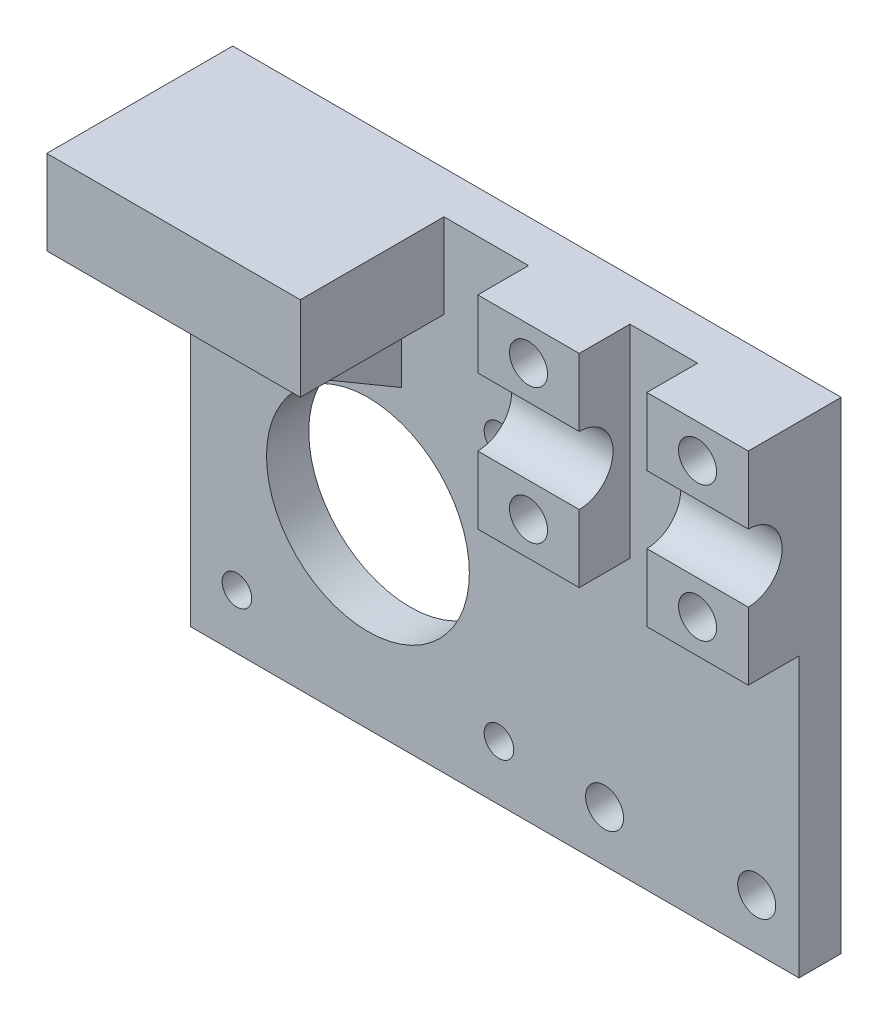
SolidWorks part; units mm, degrees
material "Printed PLA"
ref_plane "Front Plane" through (0, 0, 0) normal (0, 0, 1) x (1, 0, 0)
ref_plane "Top Plane" through (0, 0, 0) normal (0, 1, 0) x (1, 0, 0)
ref_plane "Right Plane" through (0, 0, 0) normal (1, 0, 0) x (0, 0, -1)
sketch "Sketch1" plane through (0, 0, 0) normal (0, 0, 1) x (1, 0, 0)
  line L0 (-56, 28.5) -> (16, -28.5) construction
  line L1 (-56, 28.5) -> (16, 28.5)
  line L2 (-56, 28.5) -> (-56, -28.5)
  line L3 (-56, -28.5) -> (16, -28.5)
  line L4 (16, 28.5) -> (16, -28.5)
  line L5 (-20, 0) -> (0, 0) construction
  dimension "D1" = 72
  dimension "D2" = 57
  dimension "D3" = 20
extrude "Boss-Extrude1" add sketch "Sketch1" along normal blind 5
sketch "Sketch3" plane through (16, 0, 0) normal (1, 0, 0) x (0, 0, -1)
  line L0 (-5, 28.5) -> (-11, 28.5)
  line L1 (-11, 28.5) -> (-11, 20.5)
  line L2 (-11, 12.5) -> (-11, 4.5)
  line L3 (-11, 4.5) -> (-5, 4.5)
  line L4 (-5, -28.5) -> (-5, 28.5) construction
  line L5 (-5, 4.5) -> (-5, 28.5)
  arc A0 (-11, 20.5) -> (-11, 12.5) centre (-11, 16.5) cw
  dimension "D1" = 4
  dimension "D2" = 8
  dimension "D3" = 6
extrude "Boss-Extrude2" add sketch "Sketch3" against normal blind 12
sketch "Sketch5" plane through (0, 0, 11) normal (0, 0, 1) x (1, 0, 0)
  line L0 (10, 8.5) -> (10, 24.5) construction
  line L1 (10, 16.5) -> (16, 16.5) construction
  line L2 (16, 12.5) -> (16, 20.5) construction
  line L3 (10, 24.5) -> (10, 28.5) construction
  line L4 (4, 28.5) -> (16, 28.5) construction
  circle A0 centre (10, 24.5) radius 2.25
  circle A1 centre (10, 8.5) radius 2.25
  dimension "D1" = 4.5
  dimension "D2" = 16
extrude "Cut-Extrude2" cut sketch "Sketch5" against normal through all
mirror "Mirror1" about plane through (0, 0, 0) normal (1, 0, 0) of "Cut-Extrude2", "Boss-Extrude2"
sketch "Sketch4" plane through (0, 0, 5) normal (0, 0, 1) x (1, 0, 0)
  line L0 (-56, -28.5) -> (16, -28.5) construction
  line L1 (-35, -6.5) -> (-35, -28.5) construction
  line L2 (-50.5, -22) -> (-50.5, 9) construction
  line L3 (-50.5, 9) -> (-19.5, 9) construction
  line L4 (-19.5, 9) -> (-19.5, -22) construction
  line L5 (-19.5, -22) -> (-50.5, -22) construction
  line L6 (-50.5, -22) -> (-19.5, 9) construction
  line L7 (-56, 28.5) -> (-56, -28.5) construction
  circle A0 centre (-35, -6.5) radius 12
  circle A1 centre (-50.5, 9) radius 1.75
  circle A2 centre (-19.5, 9) radius 1.75
  circle A3 centre (-19.5, -22) radius 1.75
  circle A4 centre (-50.5, -22) radius 1.75
  dimension "D2" = 24
  dimension "D4" = 3.5
  dimension "D1" = 22
  dimension "D3" = 31
  dimension "D5" = 21
extrude "Cut-Extrude1" cut sketch "Sketch4" against normal through all
sketch "Sketch6" plane through (0, 0, 5) normal (0, 0, 1) x (1, 0, 0)
  line L0 (11, -22.5) -> (-7, -22.5) construction
  line L1 (-56, -28.5) -> (16, -28.5) construction
  line L2 (2, -22.5) -> (2, -17.3253) construction
  line L3 (16, -28.5) -> (16, 4.5) construction
  circle A0 centre (-7, -22.5) radius 2.25
  circle A1 centre (11, -22.5) radius 2.25
  dimension "D1" = 4.5
  dimension "D2" = 18
  dimension "D3" = 6
  dimension "D4" = 14
extrude "Cut-Extrude3" cut sketch "Sketch6" against normal through all
sketch "Sketch7" plane through (0, 0, 5) normal (0, 0, 1) x (1, 0, 0)
  line L1 (-56, 28.5) -> (-26, 28.5)
  line L2 (-56, 28.5) -> (-56, 18.5)
  line L3 (-56, 18.5) -> (-26, 18.5)
  line L4 (-26, 28.5) -> (-26, 18.5)
  dimension "D1" = 30
  dimension "D2" = 10
extrude "Boss-Extrude3" add sketch "Sketch7" along normal blind 17
sketch "Sketch8" plane through (-26, 0, 0) normal (1, 0, 0) x (0, 0, -1)
  line L0 (-22, 18.5) -> (-5, 8.5)
  line L1 (-22, 18.5) -> (-5, 18.5) construction
  line L2 (-5, -28.5) -> (-5, 4.5) construction
  line L3 (-5, 8.5) -> (-5, 18.5)
  line L4 (-5, 18.5) -> (-22, 18.5)
  line L5 (-22, 18.5) -> (-22, 28.5) construction
  dimension "D1" = 10
extrude "Boss-Extrude4" add sketch "Sketch8" against normal blind 5 from offset 5 offset against normal yes
sketch "Sketch9" plane through (0, 0, 5) normal (0, 0, 1) x (1, 0, 0)
  line L1 (-36, 18.5) -> (-46, 18.5)
  line L2 (-36, 18.5) -> (-36, 15.5)
  line L3 (-36, 15.5) -> (-46, 15.5)
  line L4 (-46, 18.5) -> (-46, 15.5)
  dimension "D1" = 3
  dimension "D2" = 10
extrude "Cut-Extrude4" cut sketch "Sketch9" against normal through all
